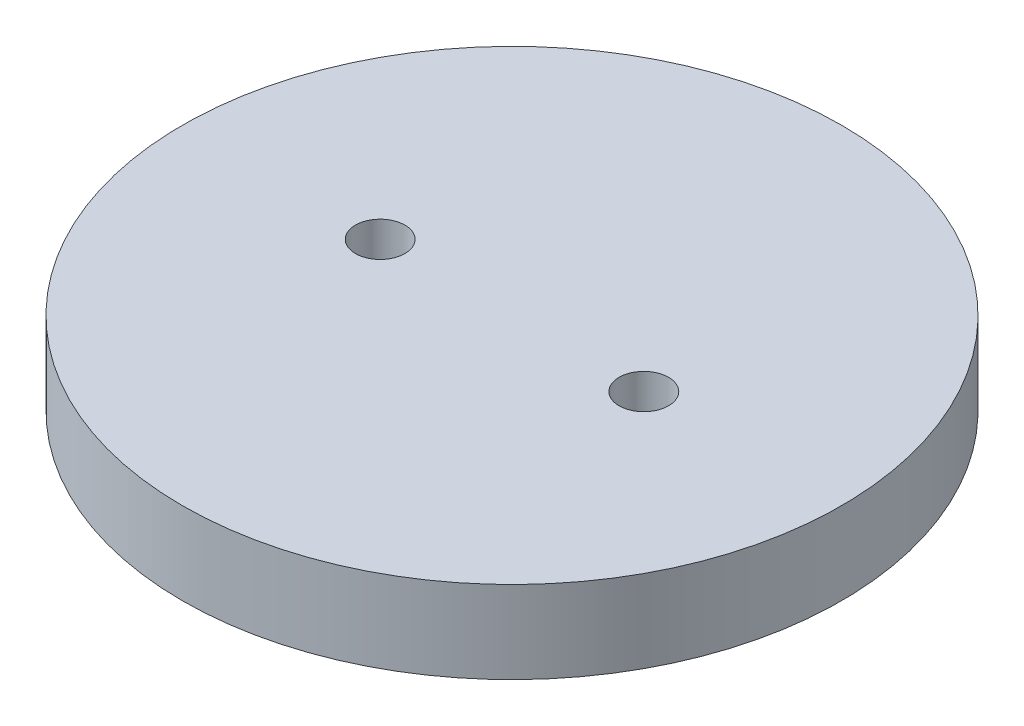
SolidWorks part; units mm, degrees
material "Acrylic (Medium-high impact)"
ref_plane "Front Plane" through (0, 0, 0) normal (0, 0, 1) x (1, 0, 0)
ref_plane "Top Plane" through (0, 0, 0) normal (0, 1, 0) x (1, 0, 0)
ref_plane "Right Plane" through (0, 0, 0) normal (1, 0, 0) x (0, 0, -1)
sketch "Sketch1" plane through (0, 0, 0) normal (0, 1, 0) x (1, 0, 0)
  circle A0 centre (0, 0) radius 20
  point P14 (0, 0)
  dimension "D1" = 40
extrude "Boss-Extrude1" add sketch "Sketch1" along normal blind 5 contours A0
sketch "Sketch2" plane through (0, 5, 0) normal (0, 1, 0) x (1, 0, 0)
  circle A0 centre (8, 0) radius 1.5
  circle A2 centre (-8, 0) radius 1.5
  circle A4 centre (0, 8) radius 1.5 [skipped]
  circle A5 centre (0, -8) radius 1.5 [skipped]
  point P12 (0, 0)
  dimension "D3" = 3
  dimension "D1" = 8
  dimension "D2" = 4
extrude "Cut-Extrude1" cut sketch "Sketch2" against normal blind 5
